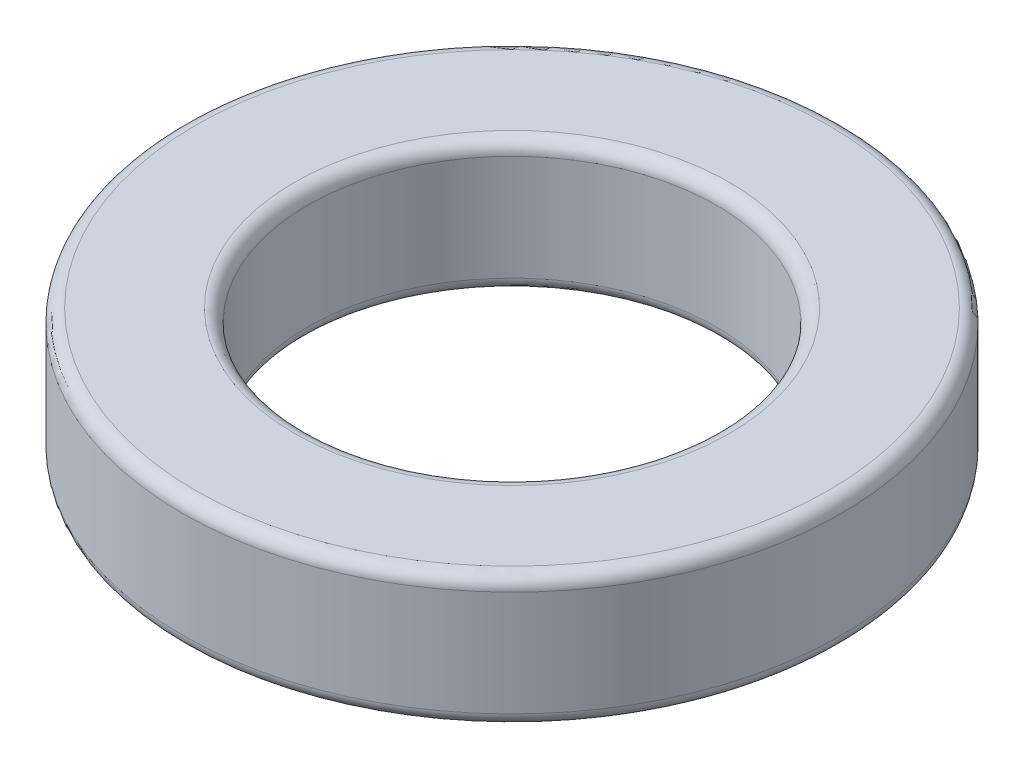
SolidWorks part; units mm, degrees
ref_plane "Front Plane" through (0, 0, 0) normal (0, 0, 1) x (1, 0, 0)
ref_plane "Top Plane" through (0, 0, 0) normal (0, 1, 0) x (1, 0, 0)
ref_plane "Right Plane" through (0, 0, 0) normal (1, 0, 0) x (0, 0, -1)
sketch "Sketch1" plane through (0, 0, 0) normal (0, 1, 0) x (1, 0, 0)
  circle A0 centre (0, 0) radius 2.5
  circle A1 centre (0, 0) radius 1.55
  dimension "D1" = 3.1
  dimension "D2" = 5
extrude "Boss-Extrude1" add sketch "Sketch1" along normal blind 1
fillet "Fillet1" radius 0.1 4 edges at (0, 0, 1.55) (0, 0, 2.5) (0, 1, 2.5) (0, 1, 1.55)
